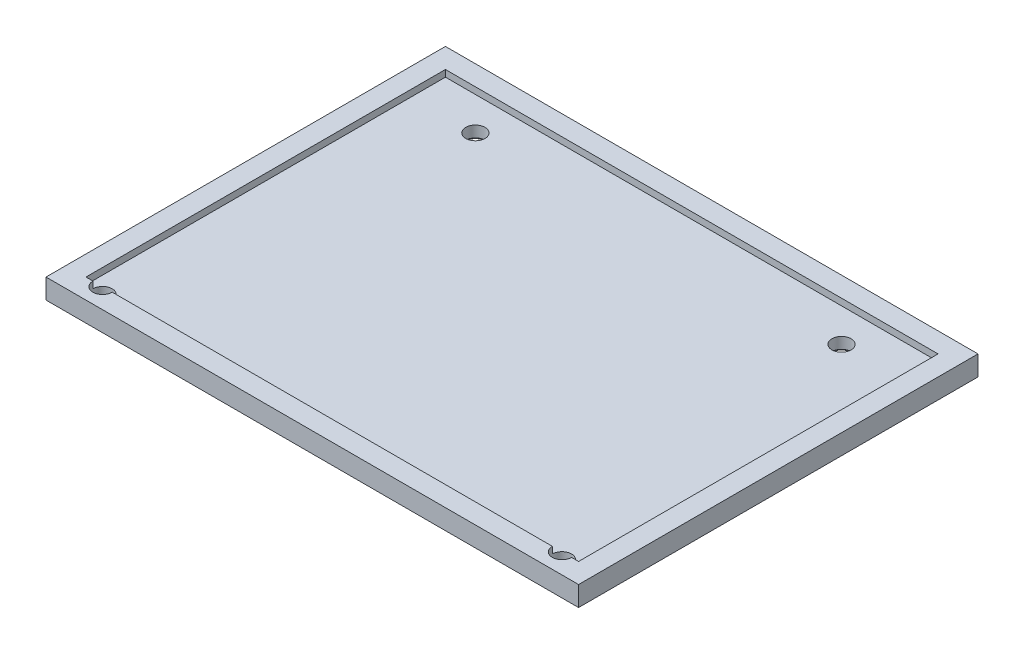
SolidWorks part; units mm, degrees
ref_plane "前视基准面" through (0, 0, 0) normal (0, 0, 1) x (1, 0, 0)
ref_plane "上视基准面" through (0, 0, 0) normal (0, 1, 0) x (1, 0, 0)
ref_plane "右视基准面" through (0, 0, 0) normal (1, 0, 0) x (0, 0, -1)
other "Configuration Table"
sketch "草图1" plane through (0, 0, 0) normal (0, 1, 0) x (1, 0, 0)
  line L1 (0, 0) -> (80, 0)
  line L2 (0, 0) -> (0, 60)
  line L3 (0, 60) -> (80, 60)
  line L4 (80, 0) -> (80, 60)
  dimension "D1" = 80
  dimension "D2" = 60
extrude "凸台-拉伸1" add sketch "草图1" along normal blind 2
sketch "草图2" plane through (0, 2, 0) normal (0, 1, 0) x (1, 0, 0)
  line L0 (80, 0) -> (80, 60) construction
  line L1 (0, 60) -> (80, 60)
  line L2 (0, 60) -> (0, 0)
  line L3 (0, 0) -> (80, 0)
  line L4 (80, 60) -> (80, 0)
  line L5 (0, 60) -> (0, 57)
  line L6 (0, 57) -> (3, 57) construction
  line L7 (40, 60) -> (40, 0) construction
  line L8 (0, 30) -> (80, 30) construction
  line L9 (80, 57) -> (77, 57) construction
  line L10 (80, 3) -> (77, 3) construction
  line L11 (0, 3) -> (3, 3) construction
  line L13 (3, 57) -> (77, 57)
  line L14 (3, 57) -> (3, 3)
  line L15 (3, 3) -> (77, 3)
  line L16 (77, 57) -> (77, 3)
  line M9 (0, 60) -> (0, 0)
  line M10 (0, 0) -> (80, 0)
  line M11 (80, 0) -> (80, 60)
  line M12 (80, 60) -> (0, 60)
  dimension "D1" = 60
  dimension "D2" = 3
  dimension "D3" = 3
extrude "凸台-拉伸2" add sketch "草图2" along normal blind 1 contours L2 L13 L16 L15 L14 M12 M9 M10 M11
sketch "草图4" plane through (0, 0, 0) normal (0, -1, 0) x (1, 0, 0)
  line L0 (0, 0) -> (80, 0) construction
  line L1 (0, 0) -> (5.5, 0) construction
  line L2 (5.5, 0) -> (5.5, -3) construction
  line L3 (40, 0) -> (40, -60) construction
  line L4 (80, -60) -> (0, -60) construction
  line L5 (0, -30) -> (80, -30) construction
  line L6 (0, -60) -> (0, 0) construction
  line L7 (80, 0) -> (80, -60) construction
  line L8 (5.5, -3) -> (5.5, -52) construction
  line L9 (0, -60) -> (12.5, -60) construction
  line L10 (12.5, -60) -> (12.5, 0) construction
  line L11 (5.5, -52) -> (81.1637, -52) construction
  circle A0 centre (5.5, -3) radius 1.75
  circle A1 centre (74.5, -3) radius 1.75
  circle A2 centre (12.5, -52) radius 1.75
  circle A3 centre (67.5, -52) radius 1.75
  point P6 (5.5, -3)
  point P17 (74.5, -3)
  point P26 (12.5, -52)
  point P29 (67.5, -52)
  point P35 (5.5, -3)
  dimension "D3" = 49
  dimension "D1" = 5.5
  dimension "D2" = 3
  dimension "D4" = 12.5
hole_wizard "M3.5 螺纹孔1" positions "草图4" profile "草图5" tap size "M3.5" standard "GB"
sketch "草图5" plane through (5.5, 0, -3) normal (1, 0, 0) x (0, 0, -1)
  line L0 (0, 0) -> (0, 9.6712)
  line L1 (0, 9.6712) -> (1.45, 8.8)
  line L2 (1.45, 8.8) -> (1.45, 0.325)
  line L3 (1.45, 0.325) -> (1.775, 0)
  line L5 (1.775, 0) -> (0, 0)
  line L6 (-1.45, 0.325) -> (-1.775, 0) construction
  line L10 (0, 9.6712) -> (-1.45, 8.8) construction
  line L11 (0, -6.35) -> (0, 107.95) construction
  dimension "螺纹孔钻头直径" = 2.9
  dimension "螺纹孔钻头深度" = 8.8
  dimension "近端锥形沉头孔直径" = 3.55
  dimension "近端锥形沉头孔角度" = 90
  dimension "导头角度" = 118
cosmetic thread "孔螺蚊线1" parameters "D1"=7, "D2"=3.5
cosmetic thread "孔螺蚊线2" parameters "D1"=7, "D2"=3.5
cosmetic thread "孔螺蚊线3" parameters "D1"=7, "D2"=3.5
cosmetic thread "孔螺蚊线4" parameters "D1"=7, "D2"=3.5
